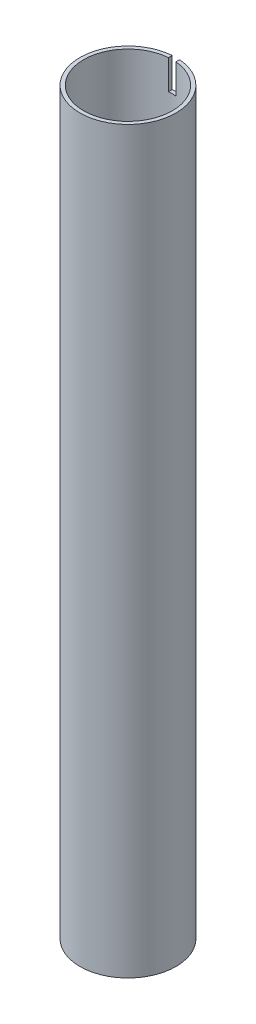
SolidWorks part; units mm, degrees
material "7075-O (SS)"
ref_plane "Front" through (0, 0, 0) normal (0, 0, 1) x (1, 0, 0)
ref_plane "Top" through (0, 0, 0) normal (0, 1, 0) x (1, 0, 0)
ref_plane "Right" through (0, 0, 0) normal (1, 0, 0) x (0, 0, -1)
sketch "Croquis1" plane through (0, 0, 0) normal (0, 1, 0) x (1, 0, 0)
  circle A0 centre (0, 0) radius 32.5
  circle A1 centre (0, 0) radius 30
  dimension "D1" = 65
  dimension "D2" = 60
extrude "Saliente-Extruir1" add sketch "Croquis1" along normal mid plane 500
sketch "Croquis2" plane through (0, 0, 0) normal (0, 0, 1) x (1, 0, 0)
  line L0 (-32.5, -250) -> (32.5, -250) construction
  line L1 (-2.5, -250) -> (2.5, -250)
  line L2 (-2.5, -250) -> (-2.5, -230)
  line L3 (-2.5, -230) -> (2.5, -230)
  line L4 (2.5, -250) -> (2.5, -230)
  line L5 (-2.5, -250) -> (2.5, -230) construction
  line L6 (-2.5, -230) -> (2.5, -250) construction
  line L7 (30, 250) -> (-30, 250) construction
  line L8 (-2.5, 230) -> (2.5, 230)
  line L9 (-2.5, 230) -> (-2.5, 250)
  line L10 (-2.5, 250) -> (2.5, 250)
  line L11 (2.5, 230) -> (2.5, 250)
  line L12 (-2.5, 230) -> (2.5, 250) construction
  line L13 (-2.5, 250) -> (2.5, 230) construction
  point P0 (0, -240)
  point P5 (0, 0)
  point P9 (0, 240)
  dimension "D1" = 20
  dimension "D2" = 5
extrude "Cortar-Extruir1" cut sketch "Croquis2" against normal up to surface (32.4037 mm away)
